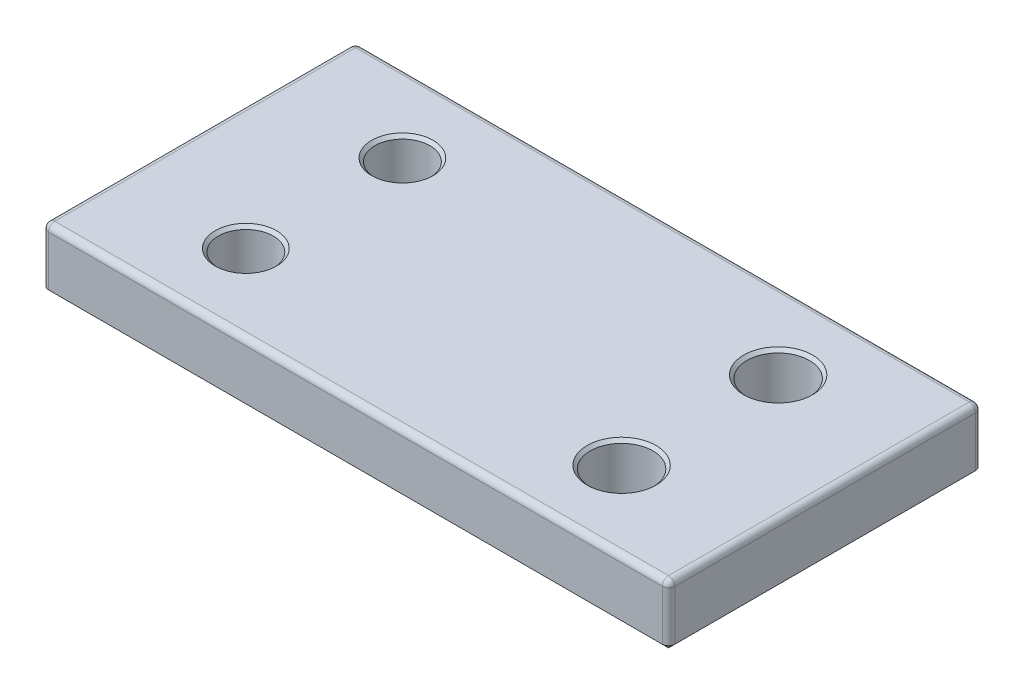
SolidWorks part; units mm, degrees
ref_plane "Front Plane" through (0, 0, 0) normal (0, 0, 1) x (1, 0, 0)
ref_plane "Top Plane" through (0, 0, 0) normal (0, 1, 0) x (1, 0, 0)
ref_plane "Right Plane" through (0, 0, 0) normal (1, 0, 0) x (0, 0, -1)
sketch "Sketch2" plane through (0, 0, 0) normal (0, 1, 0) x (1, 0, 0)
  line L1 (49, 25) -> (-49, 25)
  line L2 (50, 24) -> (50, -24)
  line L3 (49, -25) -> (-49, -25)
  line L4 (-50, 24) -> (-50, -24)
  line L5 (50, 25) -> (-50, -25) construction
  line L6 (50, -25) -> (-50, 25) construction
  arc A0 (-49, 25) -> (-50, 24) centre (-49, 24) ccw
  arc A1 (-49, -25) -> (-50, -24) centre (-49, -24) cw
  arc A2 (50, -24) -> (49, -25) centre (49, -24) cw
  arc A3 (49, 25) -> (50, 24) centre (49, 24) cw
  point P0 (0, 0)
  dimension "D3" = 1
  dimension "D4" = 1
  dimension "D1" = 100
  dimension "D2" = 50
extrude "Boss-Extrude1" add sketch "Sketch2" along normal mid plane 10
fillet "Fillet1" radius 1 8 edges at (0, 5, -25) (49.7071, 5, -24.7071) (50, 5, 0) (49.7071, 5, 24.7071) (0, 5, 25) (-49.7071, 5, 24.7071) (-50, 5, 0) (-49.7071, 5, -24.7071)
sketch "Sketch4" plane through (0, 5, 0) normal (0, 1, 0) x (1, 0, 0)
  line L0 (-30, 12.5) -> (30, 12.5) construction
  line L1 (30, 12.5) -> (30, -12.5) construction
  line L2 (30, -12.5) -> (-30, -12.5) construction
  line L3 (-30, -12.5) -> (-30, 12.5) construction
  line L7 (-50, -24) -> (-50, 24) construction
  point P4 (0, 12.5)
  point P5 (-30, 0)
  dimension "D1" = 25
  dimension "D2" = 20
chamfer "Chamfer2" distance 1 angle 45 8 edges at (-50, -5, 0) (-49.7071, -5, 24.7071) (0, -5, 25) (49.7071, -5, 24.7071) (50, -5, 0) (49.7071, -5, -24.7071) (0, -5, -25) (-49.7071, -5, -24.7071)
hole_wizard "M10x1.25 Tapped Hole1" positions "3DSketch2" profile "Sketch5" tap size "M10x1.25" standard "ISO" end condition through all
sketch3d "3DSketch2"
  point P0 (-30, 5, -12.5)
  point P3 (-30, 5, 12.5)
cosmetic thread "Hole Thread1" parameters "D2"=10
cosmetic thread "Hole Thread2" parameters "D2"=10
sketch "Sketch5" plane through (-30, 5, -12.5) normal (1, 0, 0) x (0, 0, 1)
  line L0 (0, 0) -> (0, 10)
  line L1 (0, 10) -> (4.4, 10)
  line L2 (4.4, 10) -> (4.4, 0)
  line L5 (4.4, 0) -> (0, 0)
  line L11 (0, -6.35) -> (0, 107.95) construction
  dimension "Thru Tap Drill Dia." = 8.8
  dimension "Thru Tap Drill Depth" = 10
hole_wizard "Ø10.0 (10) Diameter Hole1" positions "3DSketch3" profile "Sketch6" hole size "Ø10.0" standard "ISO" end condition through all
sketch3d "3DSketch3"
  point P0 (30, 5, -12.5)
  point P3 (30, 5, 12.5)
sketch "Sketch6" plane through (30, 5, -12.5) normal (1, 0, 0) x (0, 0, 1)
  line L0 (0, 0) -> (0, 10)
  line L1 (0, 10) -> (5, 10)
  line L2 (5, 10) -> (5, 0)
  line L5 (5, 0) -> (0, 0)
  line L11 (0, -6.35) -> (0, 107.95) construction
  dimension "Thru Hole Dia." = 10
  dimension "Thru Hole Depth" = 10
chamfer "Chamfer3" distance 0.5 angle 45 4 edges at (30, 5, 17.5) (30, 5, -7.5) (-30, 5, 16.9) (-30, 5, -8.1)
